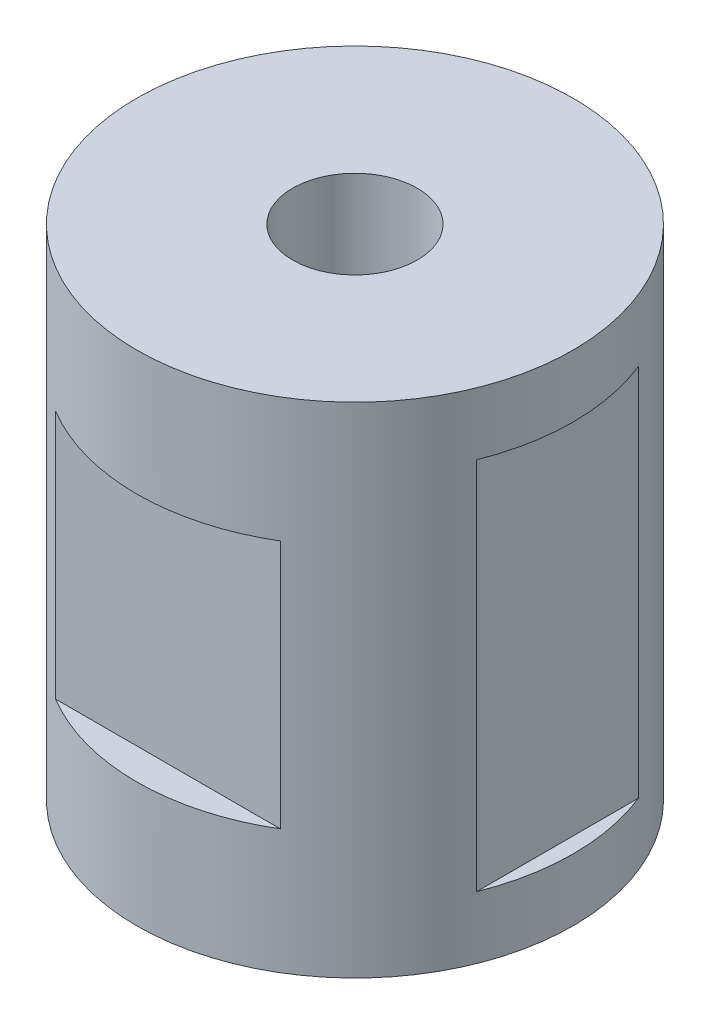
SolidWorks part; units mm, degrees
ref_plane "Front Plane" through (0, 0, 0) normal (0, 0, 1) x (1, 0, 0)
ref_plane "Top Plane" through (0, 0, 0) normal (0, 1, 0) x (1, 0, 0)
ref_plane "Right Plane" through (0, 0, 0) normal (1, 0, 0) x (0, 0, -1)
sketch "Sketch1" plane through (0, 0, 0) normal (0, 1, 0) x (1, 0, 0)
  circle A0 centre (0, 0) radius 10
  circle A1 centre (0, 0) radius 35
  dimension "D1" = 70
  dimension "D2" = 20
extrude "Boss-Extrude1" add sketch "Sketch1" along normal blind 80
ref_plane "Plane1" through (35, 0, 0) normal (1, 0, 0) x (0, 0, -1)
sketch "Sketch2" plane through (35, 0, 0) normal (1, 0, 0) x (0, 0, -1)
  line L1 (-12.99, 70) -> (12.99, 70)
  line L2 (-12.99, 70) -> (-12.99, 10)
  line L3 (-12.99, 10) -> (12.99, 10)
  line L4 (12.99, 70) -> (12.99, 10)
  point P4 (0, 10)
  dimension "D1" = 60
  dimension "D2" = 25.98
  dimension "D3" = 10
extrude "Cut-Extrude1" cut sketch "Sketch2" against normal blind 2.5
ref_plane "Plane2" through (0, 0, 35) normal (0, 0, 1) x (1, 0, 0)
sketch "Sketch3" plane through (0, 0, 35) normal (0, 0, 1) x (1, 0, 0)
  line L1 (-18.03, 60) -> (18.03, 60)
  line L2 (-18.03, 60) -> (-18.03, 20)
  line L3 (-18.03, 20) -> (18.03, 20)
  line L4 (18.03, 60) -> (18.03, 20)
  point P4 (0, 20)
  dimension "D1" = 40
  dimension "D2" = 36.06
  dimension "D3" = 20
extrude "Cut-Extrude2" cut sketch "Sketch3" against normal blind 5
